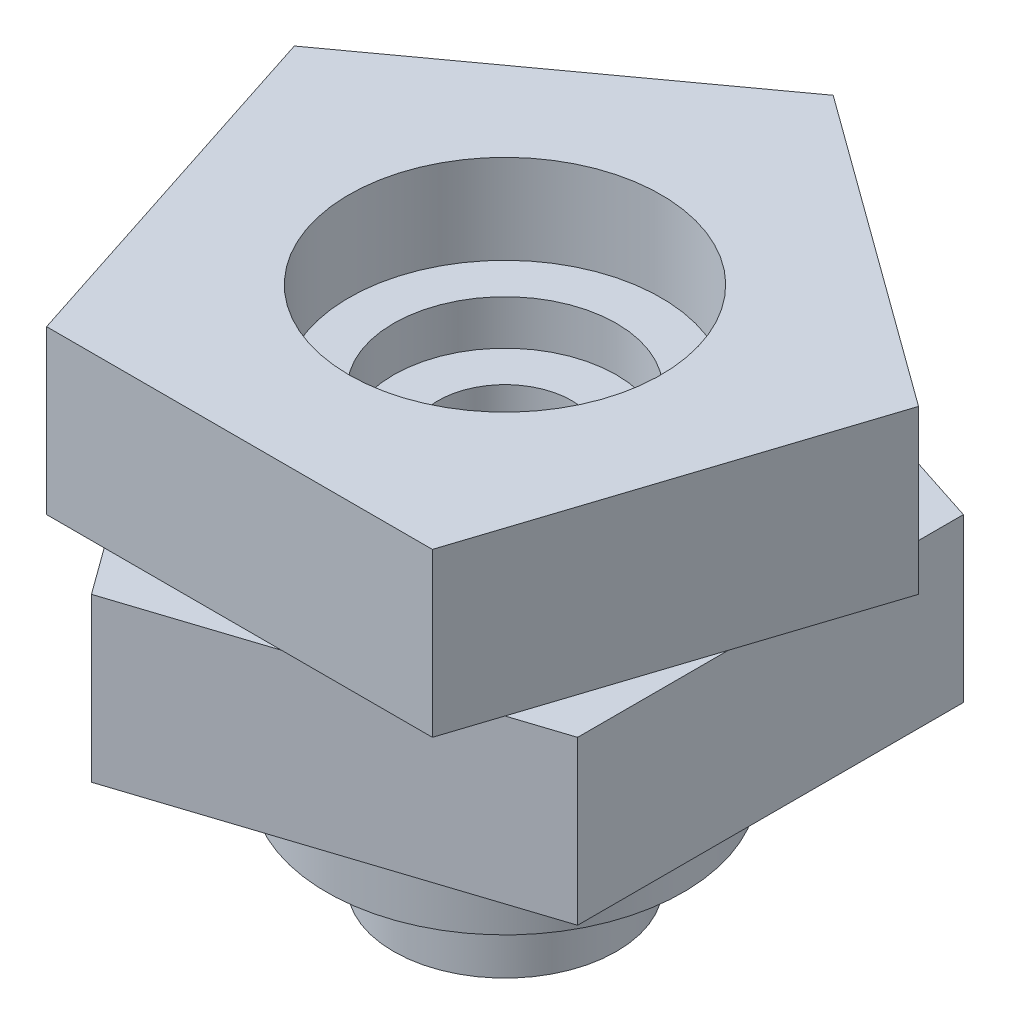
SolidWorks part; units mm, degrees
ref_plane "前视基准面" through (0, 0, 0) normal (0, 0, 1) x (1, 0, 0)
ref_plane "上视基准面" through (0, 0, 0) normal (0, 1, 0) x (1, 0, 0)
ref_plane "右视基准面" through (0, 0, 0) normal (1, 0, 0) x (0, 0, -1)
sketch "草图1" plane through (0, 0, 0) normal (0, 1, 0) x (1, 0, 0)
  line L0 (0, 7.36) -> (0, 0) construction
  line L1 (0, 7.36) -> (-6.9998, 2.2744)
  line L2 (-6.9998, 2.2744) -> (-4.3261, -5.9544)
  line L3 (-4.3261, -5.9544) -> (4.3261, -5.9544)
  line L4 (4.3261, -5.9544) -> (6.9998, 2.2744)
  line L5 (6.9998, 2.2744) -> (0, 7.36)
  circle A0 centre (0, 0) radius 7.36 construction
  dimension "D1" = 14.72
extrude "凸台-拉伸1" add sketch "草图1" along normal blind 3.65
sketch "草图2" plane through (0, 0, 0) normal (0, 1, 0) x (1, 0, 0)
  line L0 (0, 0) -> (-2.2744, -6.9998) construction
  line L11 (-2.2744, -6.9998) -> (5.9544, -4.3261)
  line L12 (5.9544, -4.3261) -> (5.9544, 4.3261)
  line L13 (5.9544, 4.3261) -> (-2.2744, 6.9998)
  line L14 (-2.2744, 6.9998) -> (-7.36, 0)
  line L15 (-7.36, 0) -> (-2.2744, -6.9998)
  line L16 (0, 0) -> (0, -7.0185) construction
  circle A0 centre (0, 0) radius 7.36 construction
  dimension "D1" = 14.72
  dimension "D2" = 18
extrude "凸台-拉伸2" add sketch "草图2" against normal blind 3.65
sketch "草图3" plane through (0, 3.65, 0) normal (0, 1, 0) x (1, 0, 0)
  circle A0 centre (0, 0) radius 3.5
  dimension "D1" = 7
extrude "切除-拉伸1" cut sketch "草图3" against normal blind 2
sketch "草图4" plane through (0, -3.65, 0) normal (0, -1, 0) x (1, 0, 0)
  circle A0 centre (0, 0) radius 4
  dimension "D1" = 8
extrude "凸台-拉伸3" add sketch "草图4" along normal blind 2.5
sketch "草图5" plane through (0, 3.65, 0) normal (0, 1, 0) x (1, 0, 0)
  line L0 (0, 7.36) -> (0, 0) construction
sketch "草图6" plane through (0, -6.15, 0) normal (0, -1, 0) x (1, 0, 0)
  line L0 (-1.299, 0.75) -> (1.299, 0.75)
  line L1 (-1.299, 0.75) -> (0, 0) construction
  line L2 (0, 0) -> (1.299, 0.75) construction
  arc A0 (-1.299, 0.75) -> (1.299, 0.75) centre (0, 0) ccw
  dimension "D1" = 3
  dimension "D2" = 120
extrude "切除-拉伸2" cut sketch "草图6" against normal through all
sketch "草图7" plane through (0, 1.65, 0) normal (0, 1, 0) x (1, 0, 0)
  circle A0 centre (0, 0) radius 2.5
  dimension "D1" = 5
extrude "切除-拉伸3" cut sketch "草图7" against normal blind 1
sketch "草图8" plane through (0, -6.15, 0) normal (0, -1, 0) x (1, 0, 0)
  line L0 (1.299, 0.75) -> (-1.299, 0.75) construction
  line L1 (1.299, 0.75) -> (-1.299, 0.75)
  arc A0 (-1.299, 0.75) -> (1.299, 0.75) centre (0, 0) ccw construction
  arc A1 (-1.299, 0.75) -> (1.299, 0.75) centre (0, 0) ccw
  circle A3 centre (0, 0) radius 2.5
  dimension "D1" = 5
extrude "凸台-拉伸4" add sketch "草图8" along normal blind 1.9
